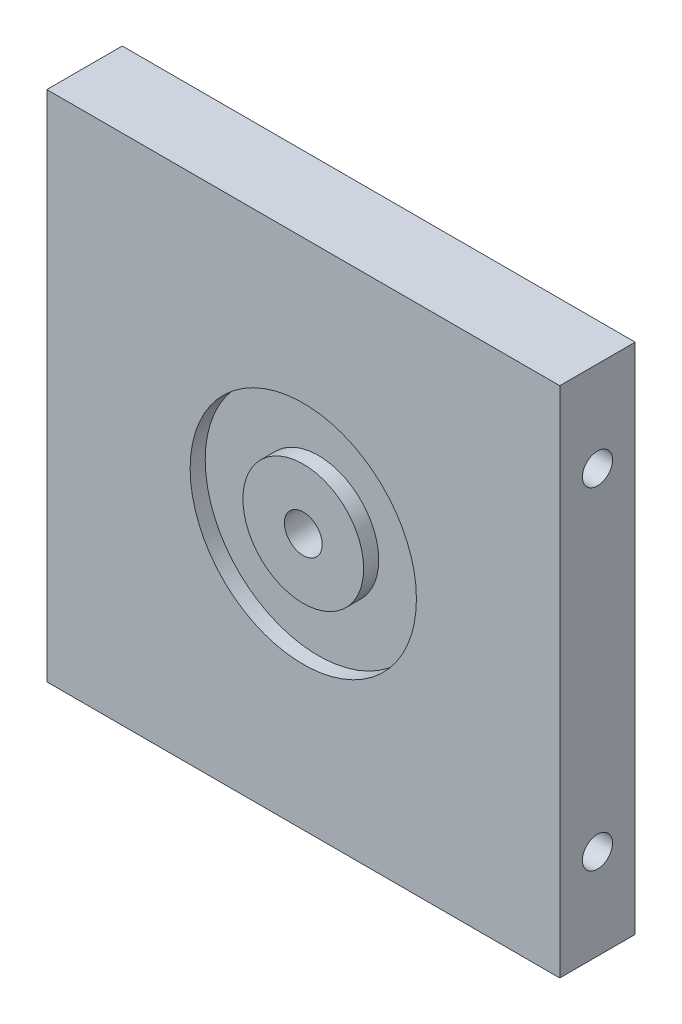
SolidWorks part; units mm, degrees
material "5052-H32"
ref_plane "Plano frontal" through (0, 0, 0) normal (0, 0, 1) x (1, 0, 0)
ref_plane "Plano superior" through (0, 0, 0) normal (0, 1, 0) x (1, 0, 0)
ref_plane "Plano direito" through (0, 0, 0) normal (1, 0, 0) x (0, 0, -1)
sketch "Esboço1" plane through (0, 0, 0) normal (0, 0, 1) x (1, 0, 0)
  line L1 (17, -17) -> (-17, -17)
  line L2 (17, -17) -> (17, 17)
  line L3 (17, 17) -> (-17, 17)
  line L4 (-17, -17) -> (-17, 17)
  line L5 (17, -17) -> (-17, 17) construction
  line L6 (17, 17) -> (-17, -17) construction
  point P0 (0, 0)
  dimension "D1" = 34
  dimension "D2" = 34
extrude "Ressalto-extrusão1" add sketch "Esboço1" along normal mid plane 5
sketch "Esboço2" plane through (0, 0, 2.5) normal (0, 0, 1) x (1, 0, 0)
  circle A0 centre (0, 0) radius 7.5
  circle A1 centre (0, 0) radius 4
  dimension "D1" = 15
  dimension "D2" = 8
extrude "Corte-extrusão1" cut sketch "Esboço2" against normal blind 1
sketch "Esboço3" plane through (0, 0, 2.5) normal (0, 0, 1) x (1, 0, 0)
  circle A0 centre (0, 0) radius 1.25
  dimension "D1" = 2.5
extrude "Corte-extrusão2" cut sketch "Esboço3" against normal up to surface (5 mm away) up to face at (0, 0, -2.5)
cosmetic thread "Representação de rosca1" parameters "D2"=3
sketch "Esboço4" plane through (-17, 0, 0) normal (-1, 0, 0) x (0, 0, 1)
  line L1 (2.5, 17) -> (-2.5, 17) construction
  circle A0 centre (0, 11) radius 1
  circle A1 centre (0, -11) radius 1
  dimension "D1" = 2
  dimension "D2" = 2
  dimension "D3" = 22
  dimension "D4" = 6
extrude "Corte-extrusão3" cut sketch "Esboço4" against normal blind 10
cosmetic thread "Representação de rosca4" parameters "D2"=2.5
cosmetic thread "Representação de rosca5" parameters "D2"=2.5
mirror "Espelhar1" about plane through (0, 0, 0) normal (1, 0, 0) of "Corte-extrusão3"
cosmetic thread "Representação de rosca2" parameters "D2"=2.5
cosmetic thread "Representação de rosca3" parameters "D2"=2.5
